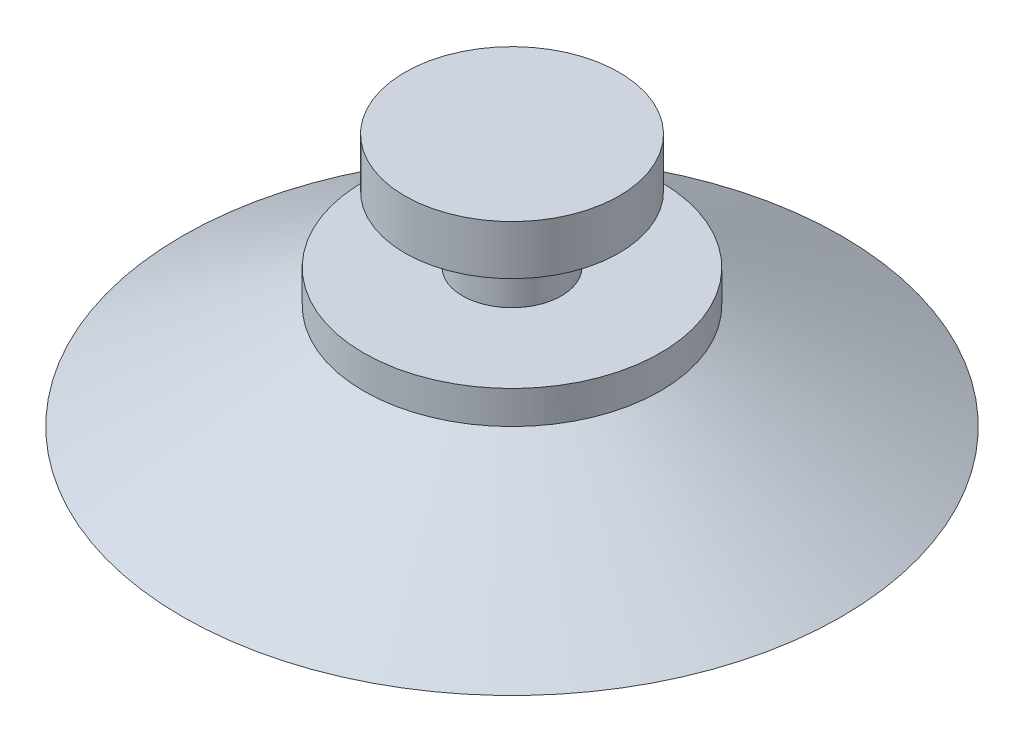
SolidWorks part; units mm, degrees
material "聚脂树脂"
ref_plane "前视基准面" through (0, 0, 0) normal (0, 0, 1) x (1, 0, 0)
ref_plane "上视基准面" through (0, 0, 0) normal (0, 1, 0) x (1, 0, 0)
ref_plane "右视基准面" through (0, 0, 0) normal (1, 0, 0) x (0, 0, -1)
other "Configuration Table"
sketch "草图1" plane through (0, 0, 0) normal (0, 1, 0) x (1, 0, 0)
  circle A0 centre (0, 0) radius 1.5
  dimension "D1" = 3
extrude "凸台-拉伸1" add sketch "草图1" along normal blind 2
sketch "草图2" plane through (0, 0, 0) normal (0, 1, 0) x (1, 0, 0)
  circle A0 centre (0, 0) radius 3.25
  dimension "D1" = 6.5
extrude "凸台-拉伸2" add sketch "草图2" along normal blind 1.5 from surface at 2 starting at face at (0, 2, 1.5)
sketch "草图3" plane through (0, 0, 0) normal (0, 1, 0) x (1, 0, 0)
  circle A0 centre (0, 0) radius 4.5
  dimension "D1" = 9
extrude "凸台-拉伸3" add sketch "草图3" against normal blind 1
sketch "草图4" plane through (0, 0, 0) normal (0, 0, 1) x (1, 0, 0)
  line L0 (0, -1000) -> (0, 49000) construction
  line L1 (4.5, -1) -> (10, -4.1754)
  line L2 (10, -4.1754) -> (8.5, -4.1754)
  line L3 (8.5, -4.1754) -> (3, -1)
  line L4 (-4.5, -1) -> (4.5, -1) construction
  line L5 (3, -1) -> (4.5, -1)
  dimension "D1" = 10
  dimension "D2" = 1.5
  dimension "D3" = 150
revolve "旋转1" add sketch "草图4" angle 360 about L0
